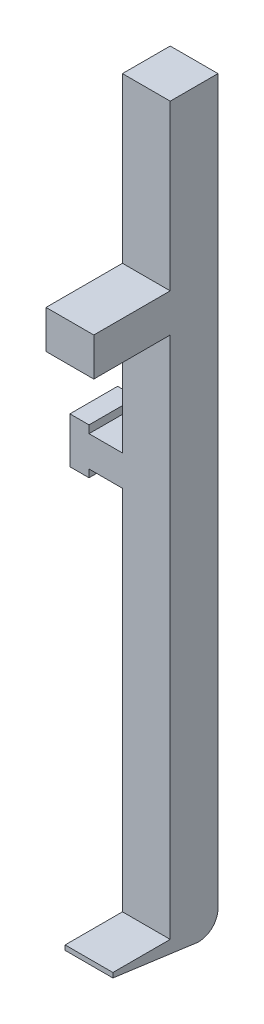
SolidWorks part; units mm, degrees
ref_plane "Front Plane" through (0, 0, 0) normal (0, 0, 1) x (1, 0, 0)
ref_plane "Top Plane" through (0, 0, 0) normal (0, 1, 0) x (1, 0, 0)
ref_plane "Right Plane" through (0, 0, 0) normal (1, 0, 0) x (0, 0, -1)
sketch "Sketch1" plane through (0, 0, 0) normal (0, 1, 0) x (1, 0, 0)
  line L1 (-1.25, -1.25) -> (1.25, -1.25)
  line L2 (-1.25, -1.25) -> (-1.25, 1.25)
  line L3 (-1.25, 1.25) -> (1.25, 1.25)
  line L4 (1.25, -1.25) -> (1.25, 1.25)
  line L5 (-1.25, -1.25) -> (1.25, 1.25) construction
  line L6 (-1.25, 1.25) -> (1.25, -1.25) construction
  point P0 (0, 0)
  dimension "D1" = 2.5
  dimension "D2" = 2.5
extrude "Boss-Extrude1" add sketch "Sketch1" along normal blind 38
sketch "Sketch2" plane through (0, 0, 1.25) normal (0, 0, 1) x (1, 0, 0)
  line L0 (1.25, 38) -> (1.25, 0) construction
  line L1 (-1.25, 0) -> (1.25, 0)
  line L2 (-1.25, 0) -> (-1.25, 1)
  line L3 (-1.25, 1) -> (1.25, 1)
  line L4 (1.25, 0) -> (1.25, 1)
  dimension "D1" = 1
extrude "Boss-Extrude2" add sketch "Sketch2" along normal blind 3
sketch "Sketch3" plane through (1.25, 0, 0) normal (1, 0, 0) x (0, 0, -1)
  line L7 (-4.25, 0) -> (-4.25, 0.75)
  line L8 (-4.25, 0) -> (-4.25, 1) construction
  line L9 (-4.25, 0.75) -> (1.25, 0)
  line L10 (1.25, 0) -> (-4.25, 0)
  dimension "D1" = 0.75
extrude "Cut-Extrude1" cut sketch "Sketch3" against normal up to vertex (2.5 mm away)
fillet "Fillet1" radius 1 1 edges at (0, 0, -1.25)
sketch "Sketch4" plane through (0, 0, 1.25) normal (0, 0, -1) x (-1, 0, 0)
  line L0 (1.25, 1) -> (1.25, 21)
  line L1 (1.25, 38) -> (1.25, 1) construction
  line L4 (1.25, 20.2) -> (1.25, 21.8)
  line L5 (1.25, 21.8) -> (3, 21.8)
  line L6 (3, 21.8) -> (3, 22.2)
  line L7 (3, 22.2) -> (4, 22.2)
  line L8 (4, 22.2) -> (4, 19.8)
  line L10 (3, 19.8) -> (4, 19.8)
  line L11 (3, 20.2) -> (3, 19.8)
  line L12 (1.25, 20.2) -> (3, 20.2)
  point P13 (4, 21)
  dimension "D1" = 20
  dimension "D2" = 0.8
  dimension "D3" = 1.75
  dimension "D4" = 1
  dimension "D5" = 1.2
extrude "Boss-Extrude4" add sketch "Sketch4" along normal up to vertex (2.5 mm away) contours L7 L8 L10 L11 L12 L4 L5 L6
sketch "Sketch6" plane through (0, 38, 0) normal (0, 1, 0) x (1, 0, 0)
  line L1 (-1.25, 1.25) -> (1.25, 1.25)
  line L2 (-1.25, 1.25) -> (-1.25, -1.25)
  line L3 (-1.25, -1.25) -> (1.25, -1.25)
  line L4 (1.25, 1.25) -> (1.25, -1.25)
extrude "Boss-Extrude5" add sketch "Sketch6" along normal blind 1
sketch "Sketch10" plane through (0, 0, 1.25) normal (0, 0, 1) x (1, 0, 0)
  line L1 (-1.25, 39) -> (-1.25, 21.8) construction
  line L2 (-1.25, 30.4) -> (1.25, 30.4)
  line L3 (-1.25, 30.4) -> (-1.25, 28.4)
  line L4 (-1.25, 28.4) -> (1.25, 28.4)
  line L5 (1.25, 30.4) -> (1.25, 28.4)
  line L6 (1.25, 39) -> (1.25, 1) construction
  dimension "D1" = 2
extrude "Boss-Extrude10" add sketch "Sketch10" along normal blind 4
